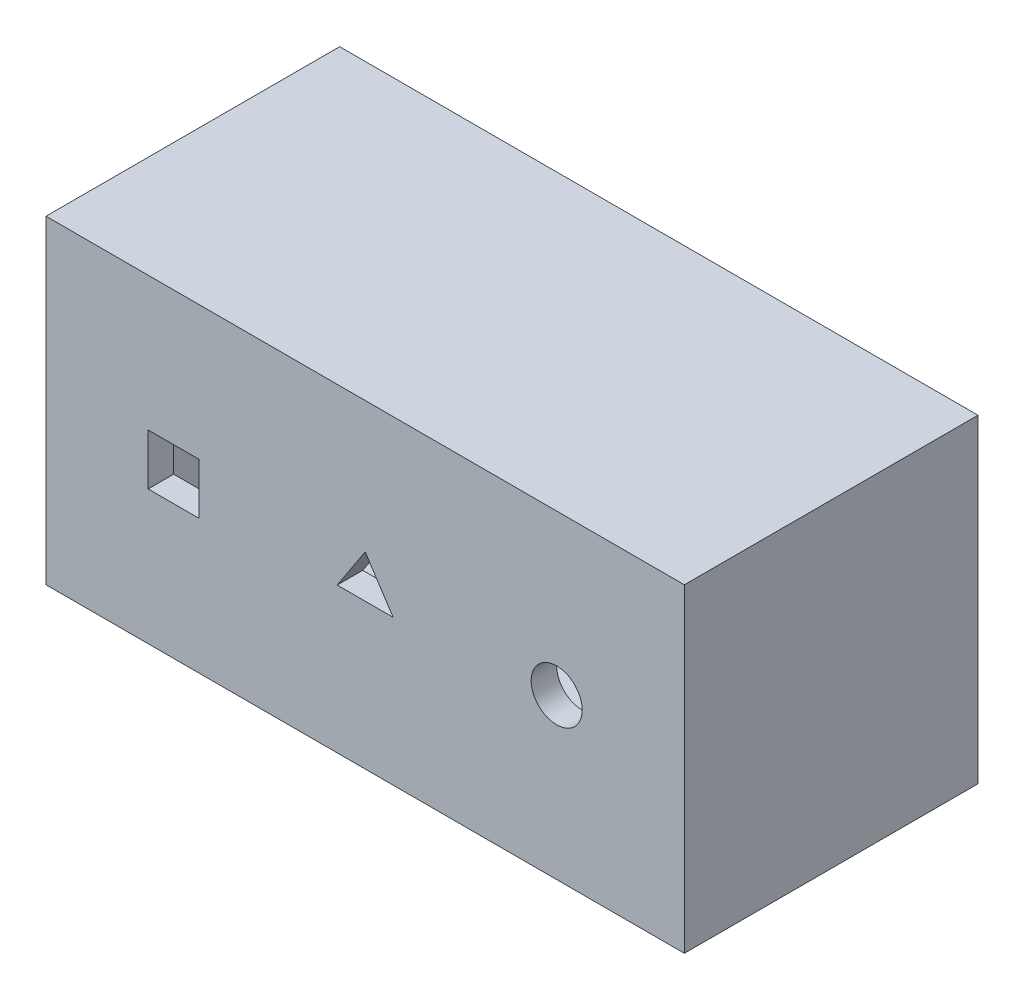
SolidWorks part; units mm, degrees
ref_plane "Front Plane" through (0, 0, 0) normal (0, 0, 1) x (1, 0, 0)
ref_plane "Top Plane" through (0, 0, 0) normal (0, 1, 0) x (1, 0, 0)
ref_plane "Right Plane" through (0, 0, 0) normal (1, 0, 0) x (0, 0, -1)
sketch "Sketch1" plane through (0, 0, 0) normal (0, 0, 1) x (1, 0, 0)
  line L1 (125, -62.5) -> (-125, -62.5)
  line L2 (125, -62.5) -> (125, 62.5)
  line L3 (125, 62.5) -> (-125, 62.5)
  line L4 (-125, -62.5) -> (-125, 62.5)
  line L5 (125, -62.5) -> (-125, 62.5) construction
  line L6 (125, 62.5) -> (-125, -62.5) construction
  line L7 (115, -57.5) -> (-115, -57.5)
  line L8 (115, -57.5) -> (115, 57.5)
  line L9 (115, 57.5) -> (-115, 57.5)
  line L10 (-115, -57.5) -> (-115, 57.5)
  line L11 (115, -57.5) -> (-115, 57.5) construction
  line L12 (115, 57.5) -> (-115, -57.5) construction
  point P0 (0, 0)
  point P6 (0, 0)
  dimension "D1" = 250
  dimension "D2" = 125
  dimension "D3" = 230
extrude "Boss-Extrude1" add sketch "Sketch1" along normal blind 100
sketch "Sketch2" plane through (0, 0, 0) normal (0, 0, -1) x (-1, 0, 0)
  line L1 (125, 62.5) -> (-125, 62.5)
  line L2 (125, 62.5) -> (125, -62.5)
  line L3 (125, -62.5) -> (-125, -62.5)
  line L4 (-125, 62.5) -> (-125, -62.5)
extrude "Boss-Extrude2" add sketch "Sketch2" along normal blind 5
sketch "Sketch3" plane through (0, 0, 100) normal (0, 0, 1) x (1, 0, 0)
  line L0 (-125, 0) -> (125, 0) construction
  line L1 (-125, 62.5) -> (125, 62.5)
  line L2 (-125, 62.5) -> (-125, -62.5)
  line L3 (-125, -62.5) -> (125, -62.5)
  line L4 (125, 62.5) -> (125, -62.5)
  line L5 (0, 62.5) -> (0, -62.5) construction
  line L6 (-10.9581, -5.5769) -> (0, 11.1539)
  line L7 (-85, 10) -> (-65, 10)
  line L8 (-85, 10) -> (-85, -10)
  line L9 (-85, -10) -> (-65, -10)
  line L10 (-65, 10) -> (-65, -10)
  line L11 (-85, 10) -> (-65, -10) construction
  line L12 (-85, -10) -> (-65, 10) construction
  line L14 (-1.3522, 0) -> (0, -1.3522)
  line L18 (0, 11.1539) -> (10.9581, -5.5769)
  line L19 (10.9581, -5.5769) -> (-10.9581, -5.5769)
  line L20 (-10.9581, -5.5769) -> (5.4791, 2.7885) construction
  line L21 (10.9581, -5.5769) -> (-5.4791, 2.7885) construction
  line L22 (0, 11.1539) -> (0, 0) construction
  circle A0 centre (75, 0) radius 10
  point P10 (-75, 0)
  point P20 (0, 0)
  point P27 (7.7505, -5.3087)
  point P28 (0, 0)
  point P29 (0, 0)
  point P30 (0, 0)
  line M21 (-125, 62.5) -> (-125, -62.5)
  line M22 (-125, -62.5) -> (125, -62.5)
  line M23 (125, -62.5) -> (125, 62.5)
  line M24 (125, 62.5) -> (-125, 62.5)
  line M25 (115, -57.5) -> (-115, -57.5)
  line M26 (-115, -57.5) -> (-115, 57.5)
  line M27 (-115, 57.5) -> (115, 57.5)
  line M28 (115, 57.5) -> (115, -57.5)
  dimension "D2" = 50
  dimension "D3" = 20
  dimension "D1" = 40
  dimension "D4" = 20
  dimension "D5" = 20
  dimension "D6" = 20
  dimension "D7" = 20
extrude "Boss-Extrude4" add sketch "Sketch3" along normal blind 10 contours A0 L7 L10 L9 L8 L18 L19 L6 M25 M28 M27 M26 | M24 M21 M22 M23 M28 M25 M26 M27
